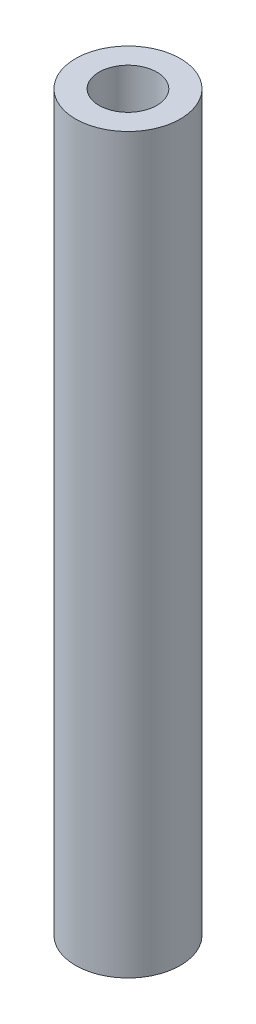
SolidWorks part; units mm, degrees
ref_plane "Front Plane" through (0, 0, 0) normal (0, 0, 1) x (1, 0, 0)
ref_plane "Top Plane" through (0, 0, 0) normal (0, 1, 0) x (1, 0, 0)
ref_plane "Right Plane" through (0, 0, 0) normal (1, 0, 0) x (0, 0, -1)
sketch "Sketch1" plane through (0, 0, 0) normal (0, 1, 0) x (1, 0, 0)
  circle A0 centre (0, 0) radius 3.175
  circle A1 centre (0, 0) radius 1.7526
  dimension "D1" = 6.35
  dimension "D2" = 3.5052
extrude "Boss-Extrude1" add sketch "Sketch1" along normal blind 44.45
